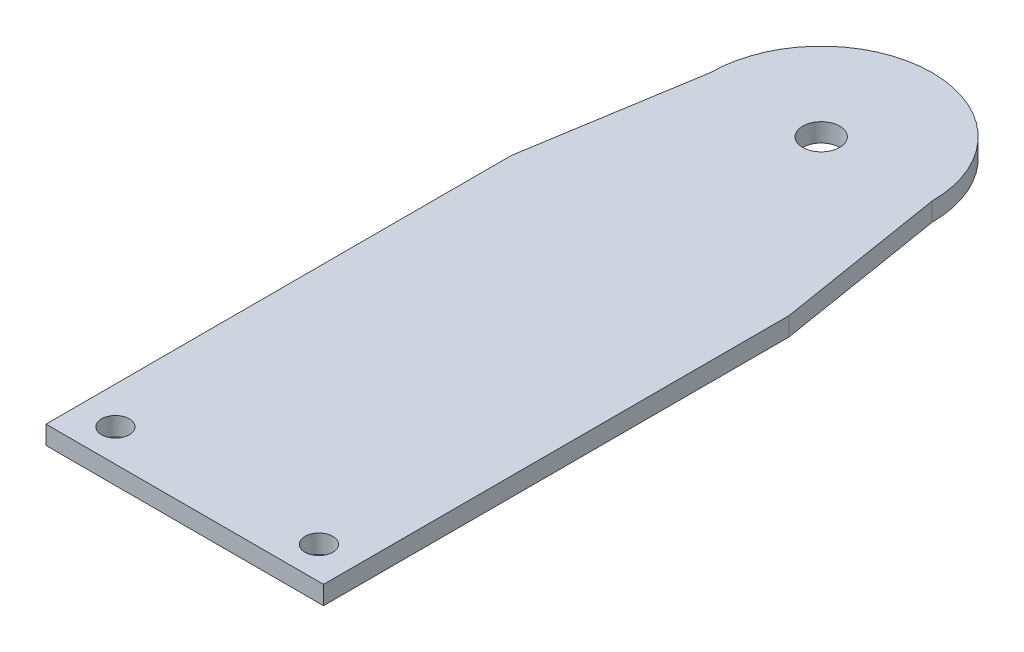
SolidWorks part; units mm, degrees
ref_plane "Спереди" through (0, 0, 0) normal (0, 0, 1) x (1, 0, 0)
ref_plane "Сверху" through (0, 0, 0) normal (0, 1, 0) x (1, 0, 0)
ref_plane "Справа" through (0, 0, 0) normal (1, 0, 0) x (0, 0, -1)
sketch "Эскиз1" plane through (0, 0, 0) normal (0, 1, 0) x (1, 0, 0)
  line L0 (-17.6252, -26.1173) -> (12.3748, -26.1173) construction
  line L1 (-17.6252, -29.6173) -> (12.3748, -29.6173) construction
  line L2 (-17.6252, -29.6173) -> (-17.6252, 48.1827) construction
  line L3 (-17.6252, 52.3827) -> (12.3748, 52.3827) construction
  line L4 (5.3748, -19.6173) -> (5.3748, -29.6173) construction
  line L5 (-13.6252, -27.6173) -> (8.3748, -27.6173) construction
  line L6 (-2.6252, -29.6173) -> (-2.6252, 60.301) construction
  line L7 (12.3748, -29.6173) -> (12.3748, 20.6827)
  line L8 (12.3748, 20.6827) -> (9.3748, 39.1827)
  line L9 (5.3748, -19.6173) -> (-10.6252, -19.6173) construction
  line L10 (5.3748, -29.6173) -> (12.3748, -29.6173)
  line L11 (-10.6252, -19.6173) -> (-10.6252, -29.6173) construction
  line L12 (-10.6252, -29.6173) -> (-17.6252, -29.6173)
  line L13 (-10.6252, -29.6173) -> (5.3748, -29.6173)
  line L14 (-17.6252, -29.6173) -> (-17.6252, 20.6827)
  line L15 (-17.6252, 20.6827) -> (-14.6252, 39.1827)
  circle A0 centre (-13.6252, -26.1173) radius 1.5
  circle A1 centre (8.3748, -26.1173) radius 1.5
  circle A2 centre (-2.6252, 39.1827) radius 2
  arc A3 (9.3748, 39.1827) -> (-14.6252, 39.1827) centre (-2.6252, 39.1827) ccw
  point P23 (-2.6252, -19.6173)
  dimension "D3" = 68.8
  dimension "D4" = 4
  dimension "D7" = 3
  dimension "D8" = 7
  dimension "D1" = 3.5
  dimension "D12" = 12
  dimension "D2" = 30
  dimension "D5" = 22
  dimension "D6" = 4
  dimension "D9" = 10
  dimension "D13" = 50.3
extrude "Бобышка-Вытянуть1" add sketch "Эскиз1" along normal blind 2
